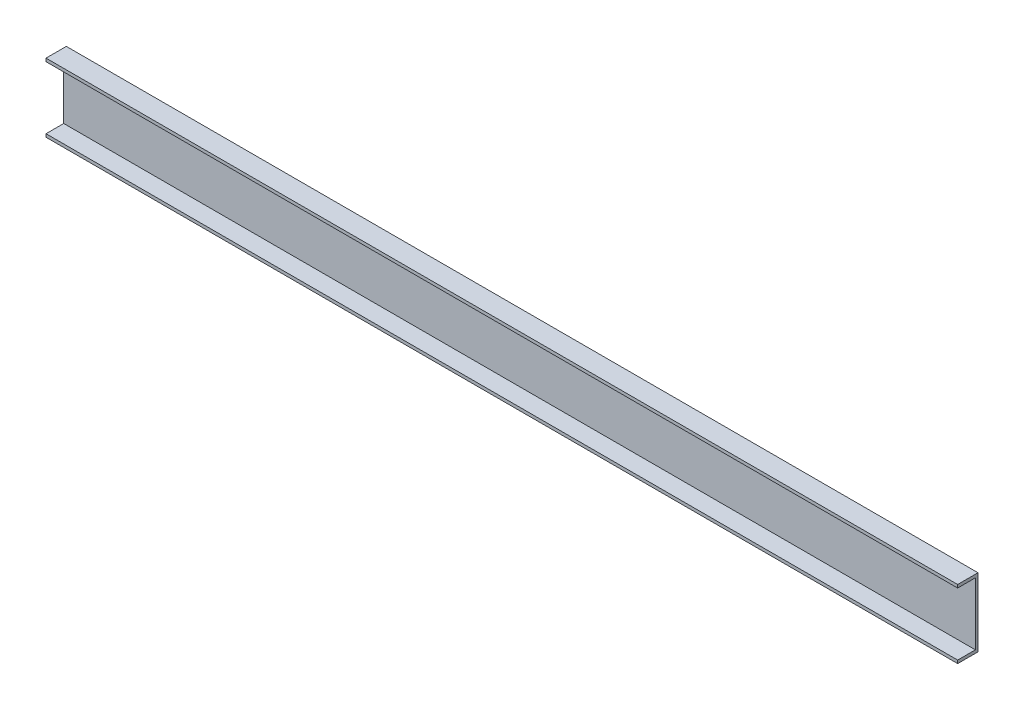
SolidWorks part; units mm, degrees
ref_plane "前视" through (0, 0, 0) normal (0, 0, 1) x (1, 0, 0)
ref_plane "上视" through (0, 0, 0) normal (0, 1, 0) x (1, 0, 0)
ref_plane "右视" through (0, 0, 0) normal (1, 0, 0) x (0, 0, -1)
sketch "草图1" plane through (0, 0, 0) normal (0, 0, 1) x (1, 0, 0)
  line L0 (-253.2778, 0) -> (2143.7198, 0) construction
  line L1 (0, 293.7967) -> (0, -293.7967) construction
  line L2 (1484.3386, 80) -> (1995, 80) construction
  line L3 (-1995, 150) -> (1995, 150)
  line L4 (-1995, 150) -> (-1995, -150)
  line L5 (-1995, -150) -> (1995, -150)
  line L6 (1995, 150) -> (1995, -150)
  line L7 (1940, 137.9179) -> (1940, -34.3032) construction
  line L8 (1860, 137.9179) -> (1860, -34.3032) construction
  line L9 (1780, -27.7215) -> (1780, 137.9179) construction
  line L10 (1700, 137.9179) -> (1700, -27.7215) construction
  line L11 (24.2318, 80) -> (382.2761, 80) construction
  line L12 (60, 137.9179) -> (60, -34.3032) construction
  line L13 (140, -34.3032) -> (140, 137.9179) construction
  dimension "D1" = 300
  dimension "D2" = 3990
  dimension "D3" = 80
  dimension "D4" = 55
  dimension "D5" = 80
  dimension "D6" = 80
  dimension "D7" = 80
  dimension "D9" = 60
  dimension "D10" = 80
extrude "基体-拉伸" add sketch "草图1" along normal blind 11.5
sketch "草图2" plane through (0, 0, 11.5) normal (0, 0, 1) x (1, 0, 0)
  line L0 (1995, -150) -> (1995, 150) construction
  line L1 (-1995, 150) -> (1995, 150)
  line L2 (-1995, 150) -> (-1995, 136.5)
  line L3 (-1995, 136.5) -> (1995, 136.5)
  line L4 (1995, 150) -> (1995, 136.5)
  line L5 (-335.9089, 0) -> (412.8346, 0) construction
  line L6 (1995, -150) -> (1995, -136.5)
  line L7 (-1995, -136.5) -> (1995, -136.5)
  line L8 (-1995, -150) -> (-1995, -136.5)
  line L9 (-1995, -150) -> (1995, -150)
  dimension "D1" = 13.5
extrude "凸台-拉伸1" add sketch "草图2" along normal blind 77.5
sketch "草图3" plane through (0, 0, 0) normal (0, 0, -1) x (-1, 0, 0)
  line L0 (-1674.4159, 0) -> (305.1386, 0) construction
  line L1 (0, 210.2636) -> (0, -302.5744) construction
  line L2 (-1995, -150) -> (-1995, 150) construction
  line L3 (-1335, 115) -> (-1265, 115)
  line L4 (-1335, 115) -> (-1335, -115)
  line L5 (-1335, -115) -> (-1265, -115)
  line L6 (-1265, 115) -> (-1265, -115)
  line L7 (-935, 115) -> (-865, 115)
  line L8 (-935, 115) -> (-935, -115)
  line L9 (-935, -115) -> (-865, -115)
  line L10 (-865, 115) -> (-865, -115)
  line L11 (-535, 115) -> (-465, 115)
  line L12 (-535, 115) -> (-535, -115)
  line L13 (-535, -115) -> (-465, -115)
  line L14 (-465, 115) -> (-465, -115)
  line L15 (465, 115) -> (465, -115)
  line L16 (535, -115) -> (465, -115)
  line L17 (535, 115) -> (535, -115)
  line L18 (535, 115) -> (465, 115)
  line L19 (865, 115) -> (865, -115)
  line L20 (935, -115) -> (865, -115)
  line L21 (935, 115) -> (935, -115)
  line L22 (935, 115) -> (865, 115)
  line L23 (1265, 115) -> (1265, -115)
  line L24 (1335, -115) -> (1265, -115)
  line L25 (1335, 115) -> (1335, -115)
  line L26 (1335, 115) -> (1265, 115)
  dimension "D1" = 70
  dimension "D2" = 70
  dimension "D3" = 70
  dimension "D4" = 230
  dimension "D5" = 660
  dimension "D6" = 400
  dimension "D7" = 400
extrude "凸台-拉伸2" add sketch "草图3" along normal blind 16
